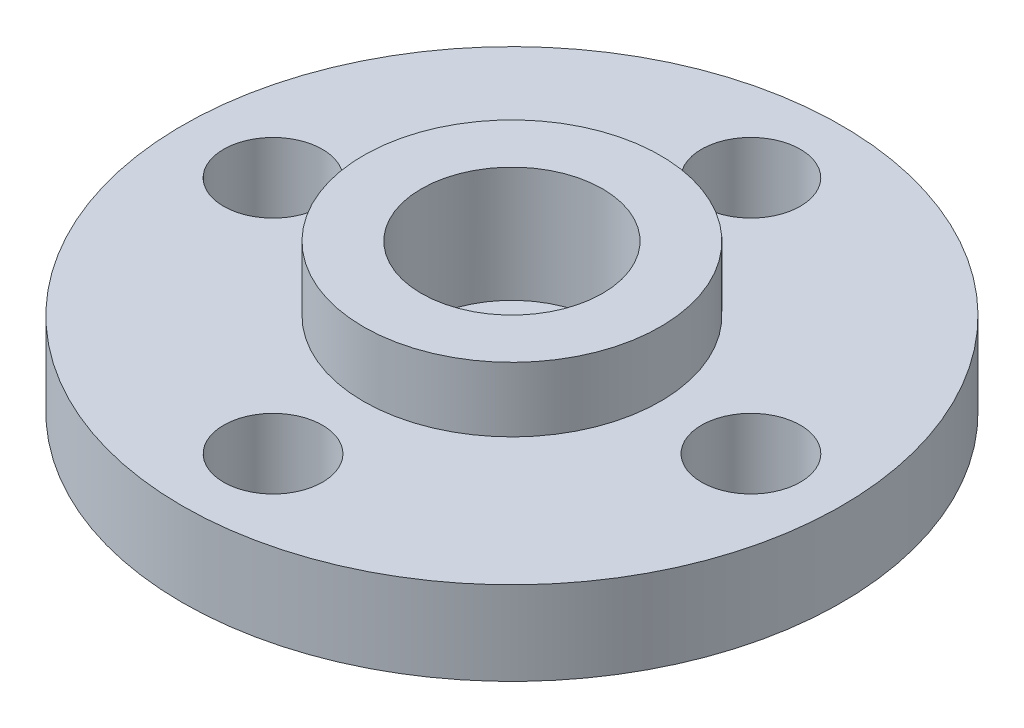
SolidWorks part; units mm, degrees
ref_plane "前视基准面" through (0, 0, 0) normal (0, 0, 1) x (1, 0, 0)
ref_plane "上视基准面" through (0, 0, 0) normal (0, 1, 0) x (1, 0, 0)
ref_plane "右视基准面" through (0, 0, 0) normal (1, 0, 0) x (0, 0, -1)
sketch "草图1" plane through (0, 0, 0) normal (0, 1, 0) x (1, 0, 0)
  circle A0 centre (0, 0) radius 10
  circle A1 centre (0, 0) radius 5.75
  circle A2 centre (0, 0) radius 7.25
  circle A3 centre (0, 0) radius 4.505
  circle A4 centre (0, 0) radius 2.75
  dimension "D1" = 20
  dimension "D2" = 11.5
  dimension "D3" = 14.5
  dimension "D4" = 9.01
  dimension "D5" = 5.5
sketch "草图2" plane through (0, 0, 0) normal (0, 1, 0) x (1, 0, 0)
  circle A0 centre (0, 0) radius 10 construction
  circle A1 centre (0, 0) radius 4.505 construction
  circle A2 centre (0, 0) radius 10
  circle A3 centre (0, 0) radius 4.505
  dimension "D1" = 9.01
  dimension "D2" = 20
extrude "凸台-拉伸1" add sketch "草图2" along normal blind 2.54
sketch "草图3" plane through (0, 0, 0) normal (0, 1, 0) x (1, 0, 0)
  circle A0 centre (0, 0) radius 2.75 construction
  circle A1 centre (0, 0) radius 4.505 construction
  circle A2 centre (0, 0) radius 2.75
  circle A3 centre (0, 0) radius 4.505
extrude "凸台-拉伸2" add sketch "草图3" along normal blind 4.5
sketch "草图4" plane through (0, 0, 0) normal (0, 1, 0) x (1, 0, 0)
  line L0 (0, 0) -> (13.8252, 0)
  line L1 (0, 0) -> (0, 8.75)
  circle A2 centre (0, 0) radius 8.75
  circle A3 centre (0, 0) radius 5.75
  circle A4 centre (0, 7.25) radius 1.5
  circle A5 centre (0, 0) radius 7.25
  circle A6 centre (7.251, 0.001) radius 1.5
  circle A7 centre (0.002, -7.25) radius 1.5
  circle A8 centre (-7.249, -0.001) radius 1.5
  point P18 (0.001, 0)
  dimension "D1" = 17.5
  dimension "D2" = 11.5
  dimension "D3" = 3
  dimension "D4" = 4
sketch "草图5" plane through (0, 0, 0) normal (0, 1, 0) x (1, 0, 0)
  circle A0 centre (-7.249, -0.001) radius 1.5 construction
  circle A1 centre (0, 7.25) radius 1.5 construction
  circle A2 centre (7.251, 0.001) radius 1.5 construction
  circle A3 centre (0.002, -7.25) radius 1.5 construction
  circle A4 centre (-7.249, -0.001) radius 1.5
  circle A5 centre (0, 7.25) radius 1.5
  circle A6 centre (7.251, 0.001) radius 1.5
  circle A7 centre (0.002, -7.25) radius 1.5
extrude "切除-拉伸1" cut sketch "草图5" along normal up to surface (2.54 mm away) up to face at (0, 2.54, 10)
ref_plane "基准面1" through (0, 0, 0) normal (0, -1, 0) x (-1, 0, 0)
sketch "草图6" plane through (0, 0, 0) normal (0, -1, 0) x (-1, 0, 0)
  circle A0 centre (0, 0) radius 2.75
  circle A1 centre (0, 0) radius 1.5
extrude "凸台-拉伸3" add sketch "草图6" against normal blind 1
sketch "草图7" plane through (0, 0, 0) normal (0, -1, 0) x (-1, 0, 0)
  circle A0 centre (0, 7.25) radius 1.5 construction
  circle A1 centre (0, 0) radius 10
  circle A2 centre (0, 0) radius 10
  circle A3 centre (7.249, -0.001) radius 1.5 construction
  circle A4 centre (-7.251, 0.001) radius 1.5 construction
  circle A5 centre (0, 0) radius 1.5 construction
  circle A6 centre (-0.002, -7.25) radius 1.5 construction
  circle A7 centre (0, 7.25) radius 1.5
  circle A8 centre (7.249, -0.001) radius 1.5
  circle A9 centre (-7.251, 0.001) radius 1.5
  circle A10 centre (0, 0) radius 1.5
  circle A11 centre (-0.002, -7.25) radius 1.5
  dimension "D1" = 0
